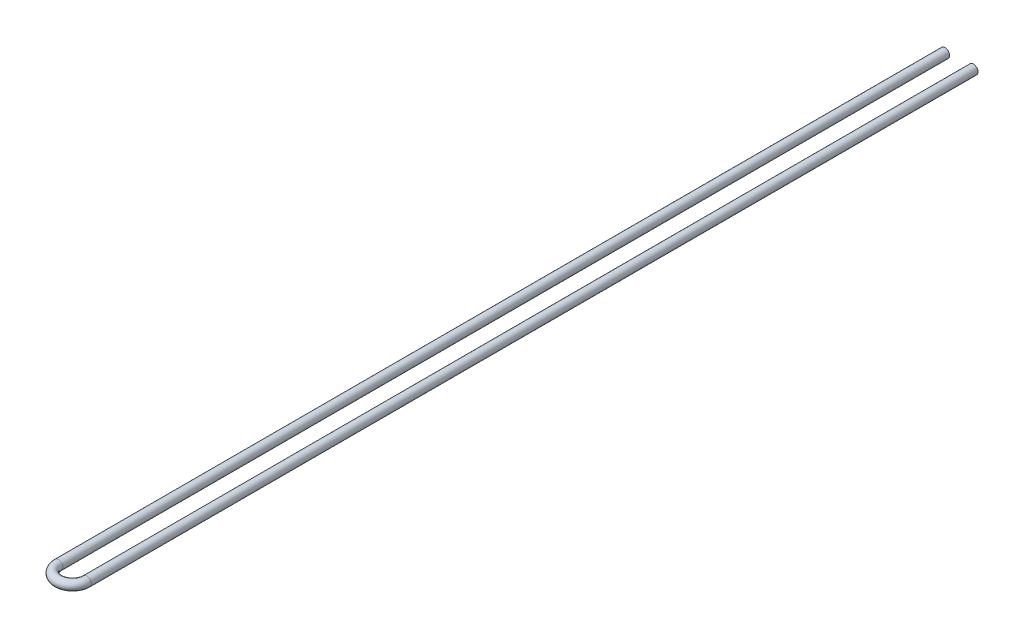
SolidWorks part; units mm, degrees
ref_plane "Front Plane" through (0, 0, 0) normal (0, 0, 1) x (1, 0, 0)
ref_plane "Top Plane" through (0, 0, 0) normal (0, 1, 0) x (1, 0, 0)
ref_plane "Right Plane" through (0, 0, 0) normal (1, 0, 0) x (0, 0, -1)
sketch "Sketch1" plane through (0, 0, 0) normal (0, 1, 0) x (1, 0, 0)
  line L0 (28.62, -300) -> (28.62, -2440)
  line L2 (-40, -300) -> (-40, -2440)
  arc A0 (-40, -2440) -> (28.62, -2440) centre (-5.69, -2440) ccw
  dimension "D1" = 2140
  dimension "D2" = 68.62
ref_plane "Plane1" through (28.62, 0, 300) normal (0, 0, -1) x (-1, 0, 0)
sketch "Sketch2" plane through (28.62, 0, 300) normal (0, 0, -1) x (-1, 0, 0)
  circle A0 centre (0, 0) radius 9.95
  circle A1 centre (0, 0) radius 11.1
  dimension "D1" = 22.2
  dimension "D2" = 19.9
sweep "Sweep1" add profiles "Sketch2" path "Sketch1"
